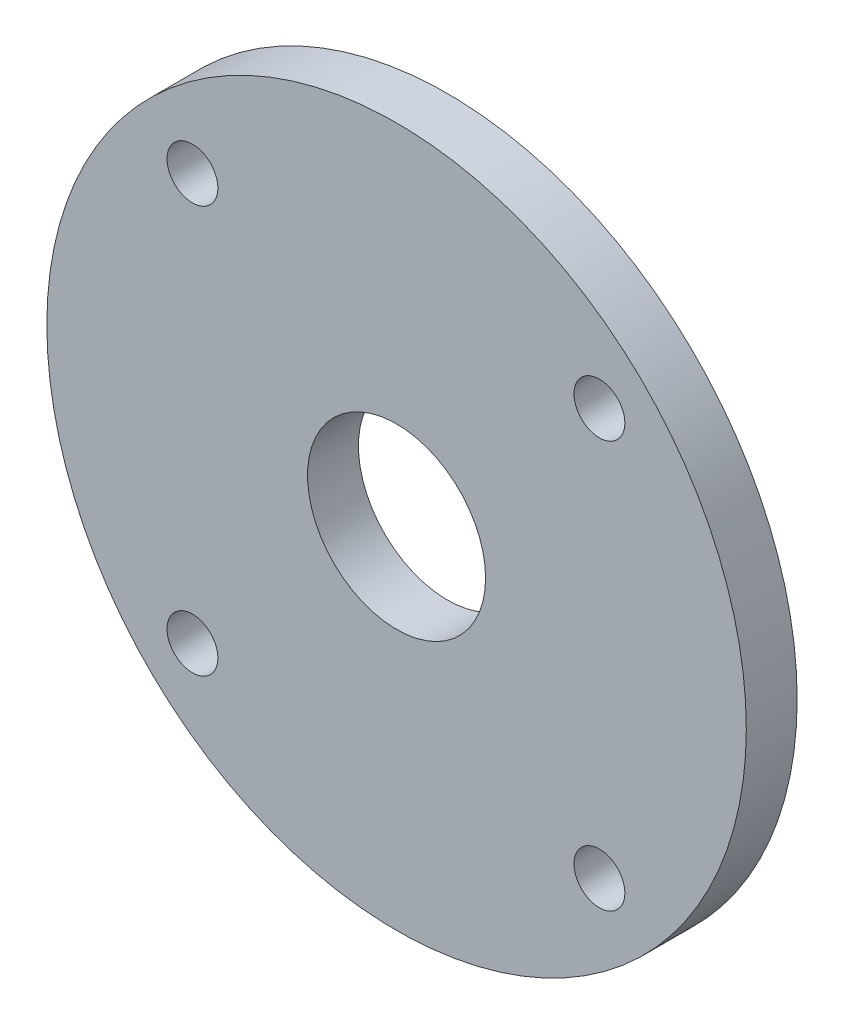
SolidWorks part; units mm, degrees
ref_plane "Front Plane" through (0, 0, 0) normal (0, 0, 1) x (1, 0, 0)
ref_plane "Top Plane" through (0, 0, 0) normal (0, 1, 0) x (1, 0, 0)
ref_plane "Right Plane" through (0, 0, 0) normal (1, 0, 0) x (0, 0, -1)
sketch "Sketch1" plane through (0, 0, 0) normal (0, 0, 1) x (1, 0, 0)
  circle A0 centre (0, 0) radius 27.5
  dimension "D1" = 55
extrude "Boss-Extrude1" add sketch "Sketch1" along normal blind 4
sketch "Sketch2" plane through (0, 0, 4) normal (0, 0, 1) x (1, 0, 0)
  arc A0 (-14.0494, 16.0247) -> (-18.0494, 16.0247) centre (-16.0494, 16.0247) ccw
  arc A1 (-18.0494, 16.0247) -> (-14.0494, 16.0247) centre (-16.0494, 16.0247) ccw
  arc A2 (-14.0494, -15.9753) -> (-18.0494, -15.9753) centre (-16.0494, -15.9753) ccw
  arc A3 (-18.0494, -15.9753) -> (-14.0494, -15.9753) centre (-16.0494, -15.9753) ccw
  arc A4 (13.9506, -15.9753) -> (17.9506, -15.9753) centre (15.9506, -15.9753) ccw
  arc A5 (17.9506, -15.9753) -> (13.9506, -15.9753) centre (15.9506, -15.9753) ccw
  arc A6 (13.9506, 16.0247) -> (17.9506, 16.0247) centre (15.9506, 16.0247) ccw
  arc A7 (17.9506, 16.0247) -> (13.9506, 16.0247) centre (15.9506, 16.0247) ccw
extrude "Cut-Extrude1" cut sketch "Sketch2" against normal blind 4
sketch "Sketch3" plane through (0, 0, 4) normal (0, 0, 1) x (1, 0, 0)
  circle A0 centre (0, 0) radius 7
  dimension "D1" = 14
extrude "Cut-Extrude2" cut sketch "Sketch3" against normal blind 4
